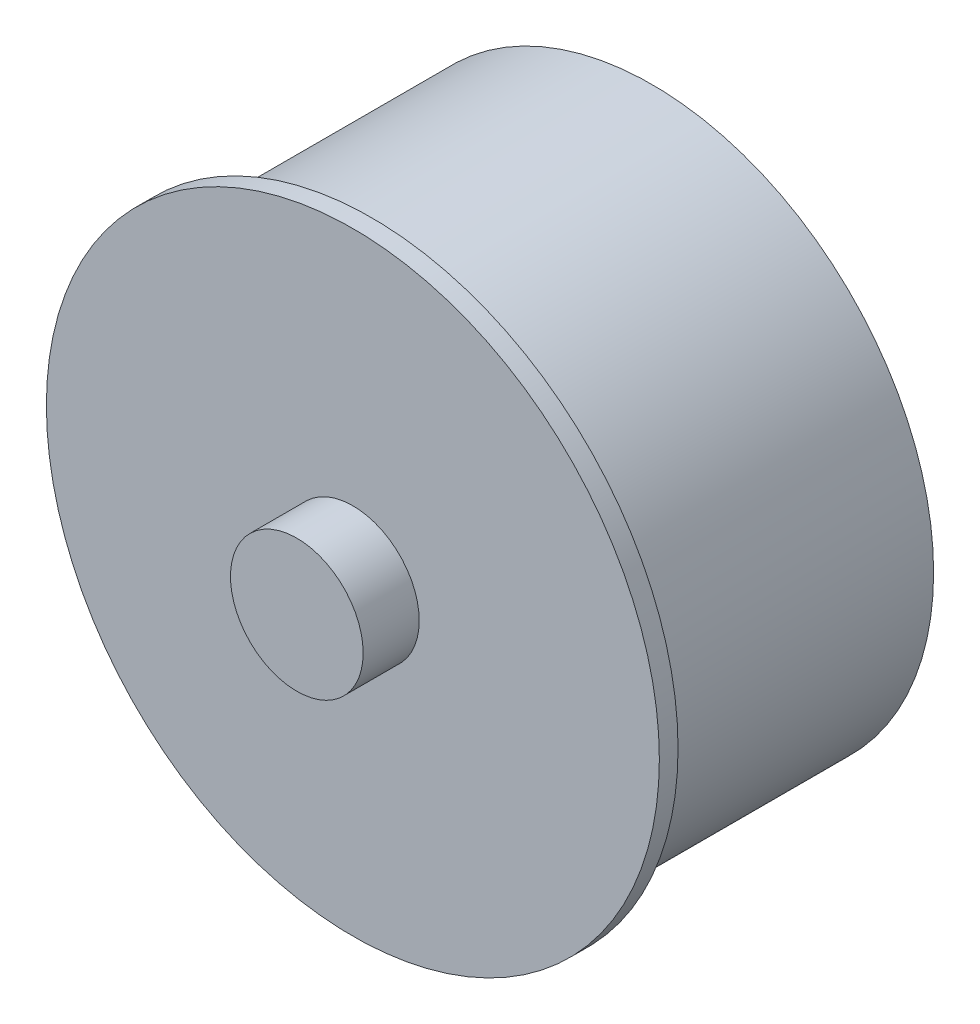
SolidWorks part; units mm, degrees
ref_plane "前视基准面" through (0, 0, 0) normal (0, 0, 1) x (1, 0, 0)
ref_plane "上视基准面" through (0, 0, 0) normal (0, 1, 0) x (1, 0, 0)
ref_plane "右视基准面" through (0, 0, 0) normal (1, 0, 0) x (0, 0, -1)
other "Configuration Table"
sketch "草图1" plane through (0, 0, 0) normal (0, 0, 1) x (1, 0, 0)
  circle A0 centre (0, 0) radius 16.4
  dimension "D1" = 32.8
extrude "凸台-拉伸1" add sketch "草图1" along normal blind 17
sketch "草图2" plane through (0, 0, 17) normal (0, 0, 1) x (1, 0, 0)
  circle A0 centre (0, 0) radius 3.55
  dimension "D1" = 7.1
extrude "凸台-拉伸2" add sketch "草图2" along normal blind 3
sketch "草图3" plane through (0, 0, 0) normal (0, 0, -1) x (-1, 0, 0)
  circle A0 centre (0, 0) radius 10.075
  dimension "D1" = 20.15
extrude "凸台-拉伸3" add sketch "草图3" along normal blind 2 separate body
sketch "草图7" plane through (0, 0, -2) normal (0, 0, -1) x (-1, 0, 0)
  line L0 (0, 0) -> (0, 8) construction
  line L1 (0, 0) -> (8, 0) construction
  line L2 (0, 0) -> (0, -8) construction
  line L3 (0, 0) -> (-8, 0) construction
  circle A0 centre (0, 8) radius 1.05
  circle A1 centre (8, 0) radius 1.05
  circle A2 centre (0, -8) radius 1.05
  circle A3 centre (-8, 0) radius 1.05
  point P13 (0, 0)
  dimension "D1" = 4
extrude "切除-拉伸3" cut sketch "草图7" against normal blind 10 contours A0 | A1 | A2 | A3
sketch "Sketch3" plane through (0, 0, 0) normal (0, 0, -1) x (-1, 0, 0)
  circle A0 centre (0, 0) radius 15.075
  circle A1 centre (0, 0) radius 16.4
extrude "Cut-Extrude1" cut sketch "Sketch3" against normal blind 16
sketch "Sketch4" plane through (0, 0, 0) normal (0, 0, -1) x (-1, 0, 0)
  circle A0 centre (0, 0) radius 10.075
  circle A1 centre (0, 0) radius 15.075
extrude "Cut-Extrude2" cut sketch "Sketch4" against normal blind 1
sketch "Sketch5" plane through (0, 0, -2) normal (0, 0, -1) x (-1, 0, 0)
  circle A0 centre (0, 0) radius 10.075
extrude "Cut-Extrude3" cut sketch "Sketch5" against normal blind 1
